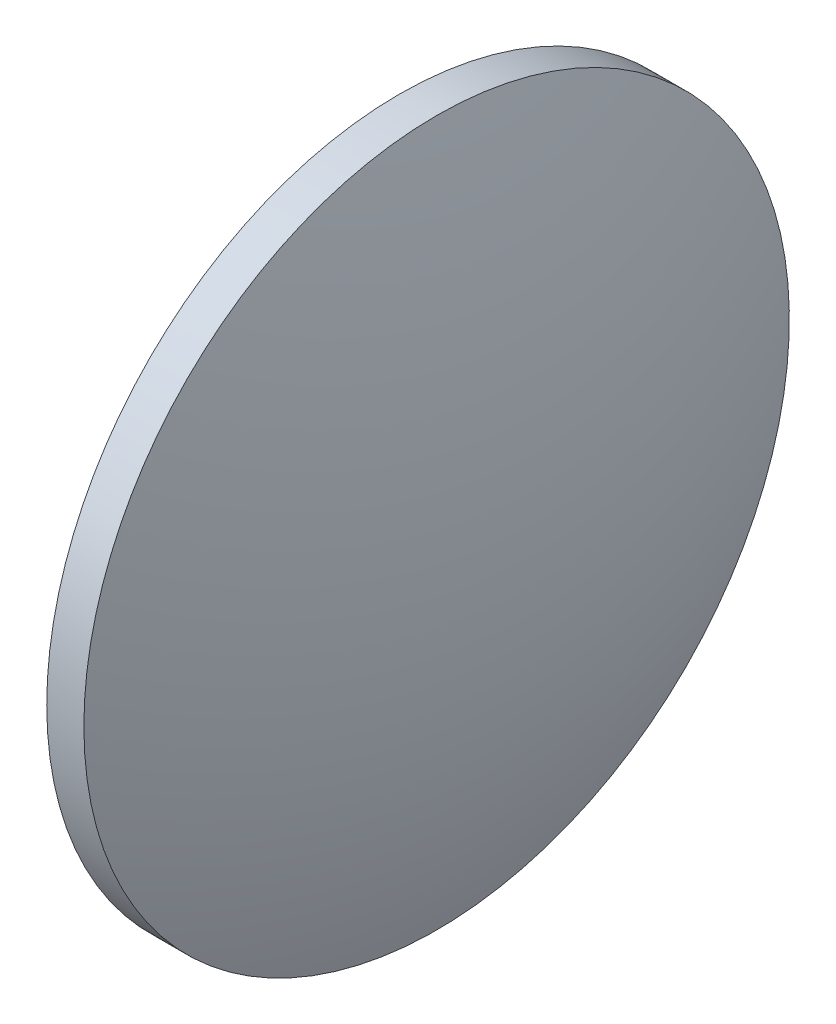
SolidWorks part; units mm, degrees
ref_plane "Front Plane" through (0, 0, 0) normal (0, 0, 1) x (1, 0, 0)
ref_plane "Top Plane" through (0, 0, 0) normal (0, 1, 0) x (1, 0, 0)
ref_plane "Right Plane" through (0, 0, 0) normal (1, 0, 0) x (0, 0, -1)
sketch "Sketch1" plane through (0, 0, 0) normal (0, 0, 1) x (1, 0, 0)
  line L0 (0, 19) -> (2, 19)
  line L2 (-3.4883, 0) -> (5.3624, 0)
  arc A0 (0, 19) -> (-3.4883, 0) centre (50, 0) ccw
  arc A1 (2, 19) -> (5.3624, 0) centre (-50, 0) cw
  dimension "D1" = 50
  dimension "D2" = 2
  dimension "D3" = 50
  dimension "D4" = 19
revolve "Revolve1" add sketch "Sketch1" angle 360 about L2
